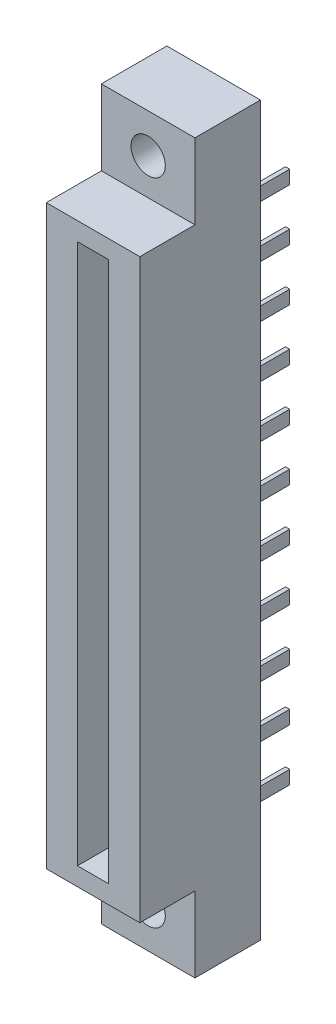
SolidWorks part; units mm, degrees
ref_plane "前视基准面" through (0, 0, 0) normal (0, 0, 1) x (1, 0, 0)
ref_plane "上视基准面" through (0, 0, 0) normal (0, 1, 0) x (1, 0, 0)
ref_plane "右视基准面" through (0, 0, 0) normal (1, 0, 0) x (0, 0, -1)
sketch "草图1" plane through (0, 0, 0) normal (0, 0, 1) x (1, 0, 0)
  line L0 (-109.3839, 0) -> (104.0581, 0) construction
  line L1 (0, 55.921) -> (0, -57.9694) construction
  line L3 (-4.5, 35) -> (4.5, 35)
  line L4 (-4.5, 35) -> (-4.5, -35)
  line L5 (-4.5, -35) -> (4.5, -35)
  line L6 (4.5, 35) -> (4.5, -35)
  dimension "D1" = 70
  dimension "D2" = 9
extrude "拉伸1" add sketch "草图1" along normal blind 6.3
sketch "草图2" plane through (0, 0, 6.3) normal (0, 0, 1) x (1, 0, 0)
  line L0 (-8.8552, 0) -> (12.3972, 0) construction
  line L1 (0, 34.0186) -> (0, -32.3951) construction
  line L3 (-4.5, 35) -> (-4.5, -35) construction
  line L4 (-4.5, 27.75) -> (4.5, 27.75)
  line L5 (-4.5, 27.75) -> (-4.5, -27.75)
  line L6 (-4.5, -27.75) -> (4.5, -27.75)
  line L7 (4.5, 27.75) -> (4.5, -27.75)
  line L8 (4.5, -35) -> (4.5, 35) construction
  dimension "D1" = 55.5
extrude "拉伸2" add sketch "草图2" along normal blind 5.3
sketch "草图3" plane through (0, 0, 6.3) normal (0, 0, 1) x (1, 0, 0)
  line L0 (-13.2827, 0) -> (15.9393, 0) construction
  line L1 (0, 37.0608) -> (0, -37.8999) construction
  circle A0 centre (0, 31.25) radius 1.65
  circle A1 centre (0, -31.25) radius 1.65
  dimension "D1" = 3.3
  dimension "D2" = 62.5
extrude "切除-拉伸1" cut sketch "草图3" against normal blind 15.3
sketch "草图4" plane through (0, 0, 0) normal (0, 0, -1) x (-1, 0, 0)
  line L0 (-14.0207, 0) -> (16.6772, 0) construction
  line L1 (0, 36.8227) -> (0, -37.1179) construction
  line L2 (1.9084, 25.6496) -> (1.9084, 24.3504)
  line L3 (-2.3187, 25.6496) -> (-1.9084, 25.6496)
  line L4 (-2.3187, 25.6496) -> (-2.3187, 24.3504)
  line L5 (-2.3187, 24.3504) -> (-1.9084, 24.3504)
  line L6 (-1.9084, 25.6496) -> (-1.9084, 24.3504)
  line L7 (2.3187, 24.3504) -> (1.9084, 24.3504)
  line L8 (2.3187, 25.6496) -> (2.3187, 24.3504)
  line L9 (2.3187, 25.6496) -> (1.9084, 25.6496)
  line L10 (2.6341, 20.6496) -> (2.2238, 20.6496)
  line L11 (-2.3187, 20.6496) -> (-2.3187, 19.3504)
  line L12 (2.6341, 19.3504) -> (2.2238, 19.3504)
  line L13 (-2.3187, 19.3504) -> (-1.9084, 19.3504)
  line L14 (-2.3187, 20.6496) -> (-1.9084, 20.6496)
  line L15 (2.2238, 20.6496) -> (2.2238, 19.3504)
  line L16 (2.6341, 20.6496) -> (2.6341, 19.3504)
  line L17 (-1.9084, 20.6496) -> (-1.9084, 19.3504)
  line L18 (2.6341, 15.6496) -> (2.2238, 15.6496)
  line L19 (-2.3187, 15.6496) -> (-2.3187, 14.3504)
  line L20 (2.6341, 14.3504) -> (2.2238, 14.3504)
  line L21 (-2.3187, 14.3504) -> (-1.9084, 14.3504)
  line L22 (-2.3187, 15.6496) -> (-1.9084, 15.6496)
  line L23 (2.2238, 15.6496) -> (2.2238, 14.3504)
  line L24 (2.6341, 15.6496) -> (2.6341, 14.3504)
  line L25 (-1.9084, 15.6496) -> (-1.9084, 14.3504)
  line L26 (2.6341, 10.6496) -> (2.2238, 10.6496)
  line L27 (-2.3187, 10.6496) -> (-2.3187, 9.3504)
  line L28 (2.6341, 9.3504) -> (2.2238, 9.3504)
  line L29 (-2.3187, 9.3504) -> (-1.9084, 9.3504)
  line L30 (-2.3187, 10.6496) -> (-1.9084, 10.6496)
  line L31 (2.2238, 10.6496) -> (2.2238, 9.3504)
  line L32 (2.6341, 10.6496) -> (2.6341, 9.3504)
  line L33 (-1.9084, 10.6496) -> (-1.9084, 9.3504)
  line L34 (2.6341, 5.6496) -> (2.2238, 5.6496)
  line L35 (-2.3187, 5.6496) -> (-2.3187, 4.3504)
  line L36 (2.6341, 4.3504) -> (2.2238, 4.3504)
  line L37 (-2.3187, 4.3504) -> (-1.9084, 4.3504)
  line L38 (-2.3187, 5.6496) -> (-1.9084, 5.6496)
  line L39 (2.2238, 5.6496) -> (2.2238, 4.3504)
  line L40 (2.6341, 5.6496) -> (2.6341, 4.3504)
  line L41 (-1.9084, 5.6496) -> (-1.9084, 4.3504)
  line L42 (2.6341, 0.6496) -> (2.2238, 0.6496)
  line L43 (-2.3187, 0.6496) -> (-2.3187, -0.6496)
  line L44 (2.6341, -0.6496) -> (2.2238, -0.6496)
  line L45 (-2.3187, -0.6496) -> (-1.9084, -0.6496)
  line L46 (-2.3187, 0.6496) -> (-1.9084, 0.6496)
  line L47 (2.2238, 0.6496) -> (2.2238, -0.6496)
  line L48 (2.6341, 0.6496) -> (2.6341, -0.6496)
  line L49 (-1.9084, 0.6496) -> (-1.9084, -0.6496)
  line L50 (-1.9084, -5.6496) -> (-1.9084, -4.3504)
  line L51 (2.6341, -5.6496) -> (2.6341, -4.3504)
  line L52 (2.2238, -5.6496) -> (2.2238, -4.3504)
  line L53 (-2.3187, -5.6496) -> (-1.9084, -5.6496)
  line L54 (-2.3187, -4.3504) -> (-1.9084, -4.3504)
  line L55 (2.6341, -4.3504) -> (2.2238, -4.3504)
  line L56 (-2.3187, -5.6496) -> (-2.3187, -4.3504)
  line L57 (2.6341, -5.6496) -> (2.2238, -5.6496)
  line L58 (-1.9084, -10.6496) -> (-1.9084, -9.3504)
  line L59 (2.6341, -10.6496) -> (2.6341, -9.3504)
  line L60 (2.2238, -10.6496) -> (2.2238, -9.3504)
  line L61 (-2.3187, -10.6496) -> (-1.9084, -10.6496)
  line L62 (-2.3187, -9.3504) -> (-1.9084, -9.3504)
  line L63 (2.6341, -9.3504) -> (2.2238, -9.3504)
  line L64 (-2.3187, -10.6496) -> (-2.3187, -9.3504)
  line L65 (2.6341, -10.6496) -> (2.2238, -10.6496)
  line L66 (-1.9084, -15.6496) -> (-1.9084, -14.3504)
  line L67 (2.6341, -15.6496) -> (2.6341, -14.3504)
  line L68 (2.2238, -15.6496) -> (2.2238, -14.3504)
  line L69 (-2.3187, -15.6496) -> (-1.9084, -15.6496)
  line L70 (-2.3187, -14.3504) -> (-1.9084, -14.3504)
  line L71 (2.6341, -14.3504) -> (2.2238, -14.3504)
  line L72 (-2.3187, -15.6496) -> (-2.3187, -14.3504)
  line L73 (2.6341, -15.6496) -> (2.2238, -15.6496)
  line L74 (-1.9084, -20.6496) -> (-1.9084, -19.3504)
  line L75 (2.6341, -20.6496) -> (2.6341, -19.3504)
  line L76 (2.2238, -20.6496) -> (2.2238, -19.3504)
  line L77 (-2.3187, -20.6496) -> (-1.9084, -20.6496)
  line L78 (-2.3187, -19.3504) -> (-1.9084, -19.3504)
  line L79 (2.6341, -19.3504) -> (2.2238, -19.3504)
  line L80 (-2.3187, -20.6496) -> (-2.3187, -19.3504)
  line L81 (2.6341, -20.6496) -> (2.2238, -20.6496)
  line L82 (2.3187, -25.6496) -> (1.9084, -25.6496)
  line L83 (2.3187, -25.6496) -> (2.3187, -24.3504)
  line L84 (2.3187, -24.3504) -> (1.9084, -24.3504)
  line L85 (-1.9084, -25.6496) -> (-1.9084, -24.3504)
  line L86 (-2.3187, -24.3504) -> (-1.9084, -24.3504)
  line L87 (-2.3187, -25.6496) -> (-2.3187, -24.3504)
  line L88 (-2.3187, -25.6496) -> (-1.9084, -25.6496)
  line L89 (1.9084, -25.6496) -> (1.9084, -24.3504)
extrude "拉伸3" add sketch "草图4" along normal blind 5
sketch "草图5" plane through (0, 0, 11.6) normal (0, 0, 1) x (1, 0, 0)
  line L0 (-15.4965, 0) -> (18.3007, 0) construction
  line L1 (0, 29.0007) -> (0, -27.75) construction
  line L2 (-4.5, -27.75) -> (4.5, -27.75) construction
  line L4 (-1.5, 26) -> (1.5, 26)
  line L5 (-1.5, 26) -> (-1.5, -26)
  line L6 (-1.5, -26) -> (1.5, -26)
  line L7 (1.5, 26) -> (1.5, -26)
  dimension "D1" = 3
  dimension "D2" = 52
extrude "切除-拉伸2" cut sketch "草图5" against normal blind 8
